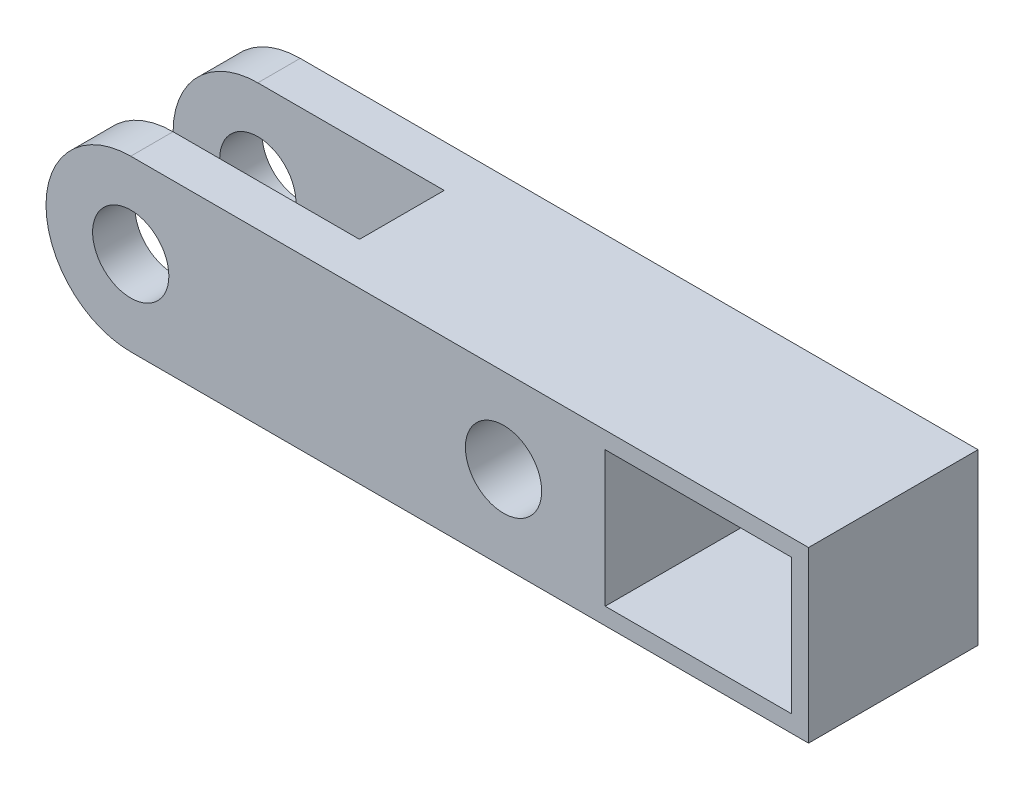
SolidWorks part; units mm, degrees
material "PET"
ref_plane "Front Plane" through (0, 0, 0) normal (0, 0, 1) x (1, 0, 0)
ref_plane "Top Plane" through (0, 0, 0) normal (0, 1, 0) x (1, 0, 0)
ref_plane "Right Plane" through (0, 0, 0) normal (1, 0, 0) x (0, 0, -1)
sketch "Sketch1" plane through (0, 0, 0) normal (0, 0, 1) x (1, 0, 0)
  line L1 (0, 5) -> (40, 5)
  line L2 (0, -5) -> (40, -5)
  line L3 (40, 5) -> (40, -5)
  arc A0 (0, 5) -> (0, -5) centre (0, 0) ccw
  circle A2 centre (0, 0) radius 2.25
  dimension "D1" = 5
  dimension "D3" = 4.5
  dimension "D2" = 40
  dimension "D4" = 10
extrude "Boss-Extrude1" add sketch "Sketch1" along normal mid plane 10
sketch "Sketch2" plane through (0, -5, 5) normal (0, 0, -1) x (1, 0, 0)
  line L3 (40, 0) -> (40, -10) construction
  circle A0 centre (22, -5) radius 2.25
  dimension "D1" = 4.5
  dimension "D2" = 18
extrude "Cut-Extrude2" cut sketch "Sketch2" along normal through all
sketch "Sketch4" plane through (0, 0, 5) normal (0, 0, -1) x (-1, 0, 0)
  line L1 (-28, -4) -> (-39, -4)
  line L2 (-28, -4) -> (-28, 4)
  line L3 (-28, 4) -> (-39, 4)
  line L4 (-39, -4) -> (-39, 4)
  line L6 (-40, 5) -> (0, 5) construction
  line L8 (-40, -5) -> (-40, 5) construction
  dimension "D1" = 8
  dimension "D2" = 11
  dimension "D3" = 1
  dimension "D4" = 1
extrude "Cut-Extrude5" cut sketch "Sketch4" along normal through all
sketch "Sketch5" plane through (0, -5, 0) normal (0, -1, 0) x (1, 0, 0)
  line L0 (-5, 5) -> (-5, -5) construction
  line L1 (-5, -2.5) -> (11, -2.5)
  line L2 (-5, -2.5) -> (-5, 2.5)
  line L3 (-5, 2.5) -> (11, 2.5)
  line L4 (11, -2.5) -> (11, 2.5)
  line L5 (40, 5) -> (40, -5) construction
  point P8 (40, 0)
  point P9 (11, 0)
  dimension "D1" = 16
  dimension "D2" = 5
extrude "Cut-Extrude6" cut sketch "Sketch5" against normal through all
